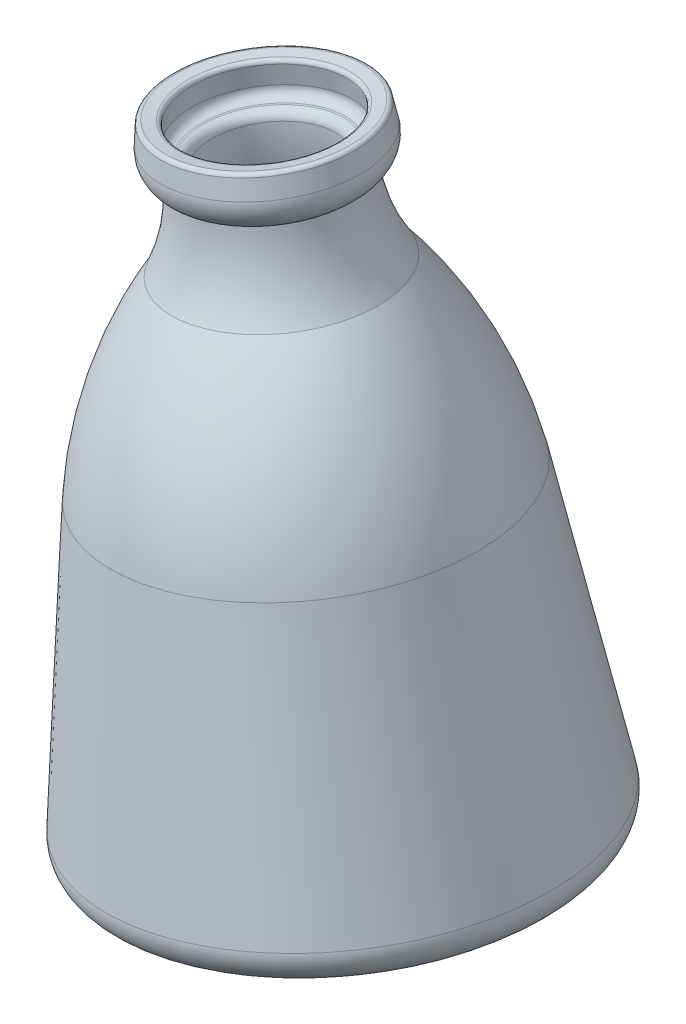
SolidWorks part; units mm, degrees
ref_plane "Front Plane" through (0, 0, 0) normal (0, 0, 1) x (1, 0, 0)
ref_plane "Top Plane" through (0, 0, 0) normal (0, 1, 0) x (1, 0, 0)
ref_plane "Right Plane" through (0, 0, 0) normal (1, 0, 0) x (0, 0, -1)
sketch "Sketch2" plane through (0, 0, 0) normal (0, 0, 1) x (1, 0, 0)
  line L0 (-0.0321, 10.0001) -> (-0.0321, 0.0001)
  line L1 (4.9679, -4.9999) -> (6.0026, -4.9999)
  line L3 (-10.0321, 10.0001) -> (-10.0321, 0.0001)
  line L4 (-21.2434, -157.3243) -> (-21.2434, -302.3243)
  line L5 (-16.2434, -307.3243) -> (33.7566, -307.3243)
  line L6 (1.5875, -14.614) -> (1.5875, -14.614)
  line L7 (-31.2434, -157.2322) -> (-31.2434, -302.3243)
  line L8 (-16.2434, -317.3243) -> (35.7718, -317.3243)
  line L9 (-8.0321, 12.0001) -> (-2.0321, 12.0001)
  line L10 (83.9933, -303.9338) -> (82.61, -294.03)
  line L11 (-0.0321, 40.0159) -> (-0.0321, 0.0001) construction
  line L12 (-10.0321, 40.0159) -> (-10.0321, 0.0001) construction
  arc A0 (10.9409, -9.217) -> (5.1514, -61.6882) centre (-87.8257, -24.8743) cw
  arc A1 (-21.2434, -157.3243) -> (5.1514, -61.6882) centre (178.7219, -161.0526) cw
  arc A2 (33.7566, -307.3243) -> (82.61, -294.03) centre (110.2767, -492.1071) cw
  arc A3 (-0.0321, 0.0001) -> (4.9679, -4.9999) centre (4.9679, 0.0001) ccw
  arc A4 (6.0026, -4.9999) -> (10.9409, -9.217) centre (6.0026, -9.9999) cw
  arc A5 (-21.2434, -302.3243) -> (-16.2434, -307.3243) centre (-16.2434, -302.3243) ccw
  arc A6 (-10.0321, 0.0001) -> (1.5875, -14.614) centre (4.9679, 0.0001) ccw
  arc A7 (1.5875, -14.614) -> (1.5875, -14.614) centre (1.5875, -14.614) cw
  arc A8 (1.5875, -14.614) -> (-3.8954, -57.3659) centre (-87.8257, -24.8743) cw
  arc A9 (-31.2434, -157.2322) -> (-3.8954, -57.3659) centre (178.7219, -161.0526) cw
  arc A10 (-31.2434, -302.3243) -> (-16.2434, -317.3243) centre (-16.2434, -302.3243) ccw
  arc A11 (35.7718, -317.3243) -> (83.9933, -303.9338) centre (110.2767, -492.1071) cw
  arc A12 (-0.0321, 10.0001) -> (-2.0321, 12.0001) centre (-2.0321, 10.0001) ccw
  arc A13 (-10.0321, 10.0001) -> (-8.0321, 12.0001) centre (-8.0321, 10.0001) cw
  point P13 (-0.0321, -4.9999)
  point P18 (-21.2434, -307.3243)
  point P43 (0, 0)
  dimension "D2" = 5
  dimension "D4" = 5
  dimension "D5" = 5
  dimension "D7" = 200
  dimension "D8" = 200
  dimension "D6" = 100
  dimension "D9" = 50
  dimension "D10" = 10
  dimension "D11" = 2
  dimension "D1" = 5
  dimension "D3" = 150
  dimension "D12" = 10
revolve "Revolve1" add sketch "Sketch2" angle 360 about L10
sketch "Sketch3" plane through (0, 0, 0) normal (1, 0, 0) x (0, 0, -1)
  line L1 (2.8789, -299.3581) -> (22.8789, -287.8111)
  line L2 (22.8789, -287.8111) -> (22.8789, -264.7171)
  line L3 (22.8789, -264.7171) -> (2.8789, -253.1701)
  line L4 (2.8789, -253.1701) -> (-17.1211, -264.7171)
  line L5 (-17.1211, -264.7171) -> (-17.1211, -287.8111)
  line L6 (-17.1211, -287.8111) -> (2.8789, -299.3581)
  circle A0 centre (2.8789, -276.2641) radius 20 construction
  dimension "D1" = 23.094
extrude "Cut-Extrude1" cut sketch "Sketch3" against normal up to next
